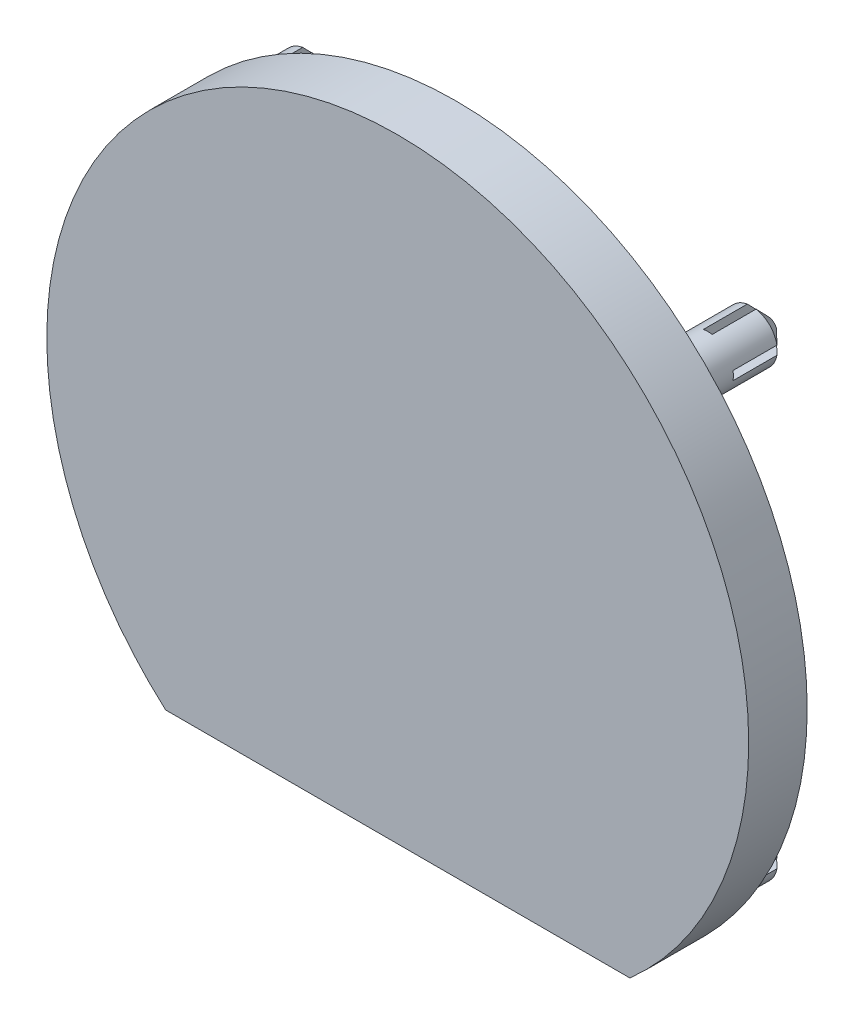
SolidWorks part; units mm, degrees
ref_plane "Front Plane" through (0, 0, 0) normal (0, 0, 1) x (1, 0, 0)
ref_plane "Top Plane" through (0, 0, 0) normal (0, 1, 0) x (1, 0, 0)
ref_plane "Right Plane" through (0, 0, 0) normal (1, 0, 0) x (0, 0, -1)
sketch "Sketch1" plane through (0, 0, 0) normal (0, 0, 1) x (1, 0, 0)
  line L0 (15.8745, -18) -> (-15.8745, -18) construction
  line L1 (15.8745, -18) -> (-15.8745, -18)
  arc A0 (15.8745, -18) -> (-15.8745, -18) centre (0, 0) ccw construction
  arc A1 (15.8745, -18) -> (-15.8745, -18) centre (0, 0) ccw
extrude "Boss-Extrude1" add sketch "Sketch1" along normal blind 4
sketch "Sketch3" plane through (0, 0, 0) normal (0, 0, -1) x (-1, 0, 0)
  circle A24 centre (-15.2028, -15.2028) radius 1.75
  circle A25 centre (-15.2028, -15.2028) radius 1.75
  circle A27 centre (15.2028, -15.2028) radius 1.75
  circle A28 centre (15.2028, -15.2028) radius 1.75
  circle A30 centre (15.2028, 15.2028) radius 1.75
  circle A31 centre (15.2028, 15.2028) radius 1.75
  circle A33 centre (-15.2028, 15.2028) radius 1.75
  circle A34 centre (-15.2028, 15.2028) radius 1.75
  dimension "D1" = 0.15
  dimension "D2" = 0.15
  dimension "D3" = 0.15
  dimension "D4" = 0.15
extrude "Boss-Extrude2" add sketch "Sketch3" along normal blind 6 separate body
chamfer "Chamfer1" distance 1 angle 45 1 edges at (13.4528, 15.2028, -6)
chamfer "Chamfer2" distance 1 angle 45 1 edges at (13.4528, -15.2028, -6)
chamfer "Chamfer3" distance 1 angle 45 1 edges at (-16.9528, 15.2028, -6)
chamfer "Chamfer4" distance 1 angle 45 1 edges at (-16.9528, -15.2028, -6)
sketch "Sketch4" plane through (0, 0, -6) normal (0, 0, -1) x (-1, 0, 0)
  line L0 (-15.2028, -17.2028) -> (-15.2028, -13.2028) construction
  line L1 (-15.5028, -13.2028) -> (-14.9028, -13.2028)
  line L2 (-15.5028, -13.2028) -> (-15.5028, -17.2028)
  line L3 (-15.5028, -17.2028) -> (-14.9028, -17.2028)
  line L4 (-14.9028, -13.2028) -> (-14.9028, -17.2028)
  line L5 (-14.9028, -15.2028) -> (-15.5028, -15.2028) construction
  line L11 (-17.2028, -15.5028) -> (-13.2028, -15.5028)
  line L12 (-17.2028, -15.5028) -> (-17.2028, -14.9028)
  line L13 (-17.2028, -14.9028) -> (-13.2028, -14.9028)
  line L14 (-13.2028, -15.5028) -> (-13.2028, -14.9028)
  line L15 (-17.2028, -15.5028) -> (-13.2028, -14.9028) construction
  line L16 (-17.2028, -14.9028) -> (-13.2028, -15.5028) construction
  line L17 (13.2028, -15.5028) -> (17.2028, -15.5028)
  line L18 (13.2028, -15.5028) -> (13.2028, -14.9028)
  line L19 (13.2028, -14.9028) -> (17.2028, -14.9028)
  line L20 (17.2028, -15.5028) -> (17.2028, -14.9028)
  line L21 (13.2028, -15.5028) -> (17.2028, -14.9028) construction
  line L22 (13.2028, -14.9028) -> (17.2028, -15.5028) construction
  line L23 (14.9028, -17.2028) -> (15.5028, -17.2028)
  line L24 (14.9028, -17.2028) -> (14.9028, -13.2028)
  line L25 (14.9028, -13.2028) -> (15.5028, -13.2028)
  line L26 (15.5028, -17.2028) -> (15.5028, -13.2028)
  line L27 (14.9028, -17.2028) -> (15.5028, -13.2028) construction
  line L28 (14.9028, -13.2028) -> (15.5028, -17.2028) construction
  line L29 (-14.9028, 17.2028) -> (-15.5028, 17.2028)
  line L30 (-14.9028, 17.2028) -> (-14.9028, 13.2028)
  line L31 (-14.9028, 13.2028) -> (-15.5028, 13.2028)
  line L32 (-15.5028, 17.2028) -> (-15.5028, 13.2028)
  line L33 (-14.9028, 17.2028) -> (-15.5028, 13.2028) construction
  line L34 (-14.9028, 13.2028) -> (-15.5028, 17.2028) construction
  line L35 (-13.2028, 14.9028) -> (-17.2028, 14.9028)
  line L36 (-13.2028, 14.9028) -> (-13.2028, 15.5028)
  line L37 (-13.2028, 15.5028) -> (-17.2028, 15.5028)
  line L38 (-17.2028, 14.9028) -> (-17.2028, 15.5028)
  line L39 (-13.2028, 14.9028) -> (-17.2028, 15.5028) construction
  line L40 (-13.2028, 15.5028) -> (-17.2028, 14.9028) construction
  line L41 (13.2028, 14.9028) -> (17.2028, 14.9028)
  line L42 (13.2028, 14.9028) -> (13.2028, 15.5028)
  line L43 (13.2028, 15.5028) -> (17.2028, 15.5028)
  line L44 (17.2028, 14.9028) -> (17.2028, 15.5028)
  line L45 (13.2028, 14.9028) -> (17.2028, 15.5028) construction
  line L46 (13.2028, 15.5028) -> (17.2028, 14.9028) construction
  line L47 (14.9028, 13.2028) -> (15.5028, 13.2028)
  line L48 (14.9028, 13.2028) -> (14.9028, 17.2028)
  line L49 (14.9028, 17.2028) -> (15.5028, 17.2028)
  line L50 (15.5028, 13.2028) -> (15.5028, 17.2028)
  line L51 (14.9028, 13.2028) -> (15.5028, 17.2028) construction
  line L52 (14.9028, 17.2028) -> (15.5028, 13.2028) construction
  circle A0 centre (-15.2028, -15.2028) radius 0.75 construction
  circle A1 centre (-15.2028, -15.2028) radius 0.75 construction
  circle A2 centre (15.2028, -15.2028) radius 0.75 construction
  circle A3 centre (15.2028, -15.2028) radius 0.75 construction
  circle A4 centre (-15.2028, 15.2028) radius 0.75 construction
  circle A5 centre (-15.2028, 15.2028) radius 0.75 construction
  circle A6 centre (15.2028, 15.2028) radius 0.75 construction
  circle A7 centre (15.2028, 15.2028) radius 0.75 construction
  point P8 (-15.2028, -15.2028)
  circle M22 centre (-15.2028, -15.2028) radius 0.75
  dimension "D1" = 0.6
  dimension "D2" = 4
  dimension "D3" = 4
  dimension "D4" = 0.6
  dimension "D5" = 0.6
  dimension "D6" = 4
  dimension "D7" = 0.6
  dimension "D8" = 4
  dimension "D9" = 0.6
  dimension "D10" = 4
  dimension "D11" = 4
  dimension "D12" = 0.6
  dimension "D13" = 0.6
  dimension "D14" = 0.6
  dimension "D15" = 4
  dimension "D16" = 4
extrude "Cut-Extrude1" cut sketch "Sketch4" against normal blind 4 contours L17 L26 L19 L24 | L26 L17 L20 L19 | L17 L24 L19 L18 | L19 L26 L25 L24 | L23 L26 L17 L24 | L13 L2 L11 L4 | L13 L4 L11 M22 | L11 L14 L13 M22 | L11 L2 L4 M22 | L4 L2 L3 M22 | L13 L11 L2 M22 | L13 L12 L11 M22 | L2 L13 L4 M22 | L4 L1 L2 M22 | L41 L50 L43 L48 | L50 L41 L44 L43 | L43 L50 L49 L48 | L41 L48 L43 L42 | L47 L50 L41 L48 | L30 L37 L32 L35 | L36 L37 L30 L35 | L37 L30 L29 L32 | L38 L35 L32 L37 | L30 L35 L32 L31
